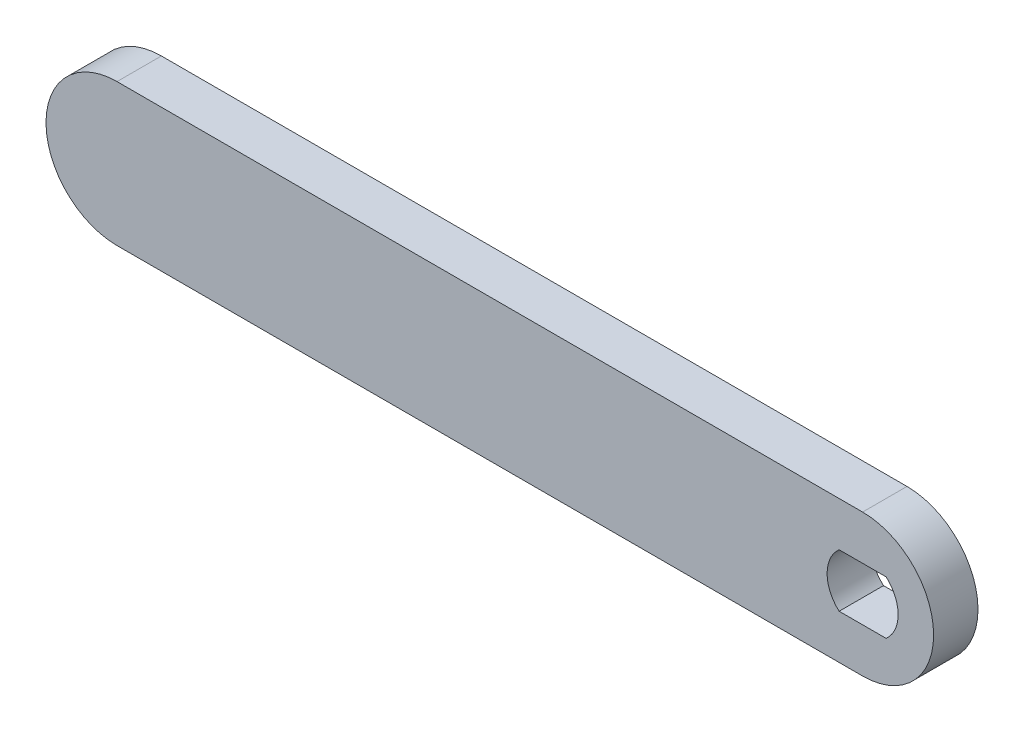
SolidWorks part; units mm, degrees
ref_plane "Front Plane" through (0, 0, 0) normal (0, 0, 1) x (1, 0, 0)
ref_plane "Top Plane" through (0, 0, 0) normal (0, 1, 0) x (1, 0, 0)
ref_plane "Right Plane" through (0, 0, 0) normal (1, 0, 0) x (0, 0, -1)
sketch "Sketch1" plane through (0, 0, 0) normal (0, 0, 1) x (1, 0, 0)
  line L0 (0, 8) -> (-84, 8)
  line L1 (-84, -8) -> (0, -8)
  line L2 (0, 3) -> (0, 4) construction
  line L3 (2.6458, 3) -> (-2.6458, 3)
  line L4 (2.6458, 3) -> (2.6458, -3)
  line L5 (2.6458, -3) -> (-2.6458, -3)
  line L6 (-2.6458, 3) -> (-2.6458, -3)
  line L7 (2.6458, 3) -> (-2.6458, -3) construction
  line L8 (2.6458, -3) -> (-2.6458, 3) construction
  line L9 (-92, 0) -> (8, 0) construction
  circle A0 centre (0, 0) radius 8
  circle A1 centre (-84, 0) radius 8
  circle A2 centre (0, 0) radius 4
  dimension "D2" = 8
  dimension "D3" = 16
  dimension "D1" = 1
  dimension "D4" = 100
extrude "Boss-Extrude1" add sketch "Sketch1" against normal blind 5 contours A1 | A1 L1 A0 L0 | A0 A2 | L3 A2 | L5 A2
